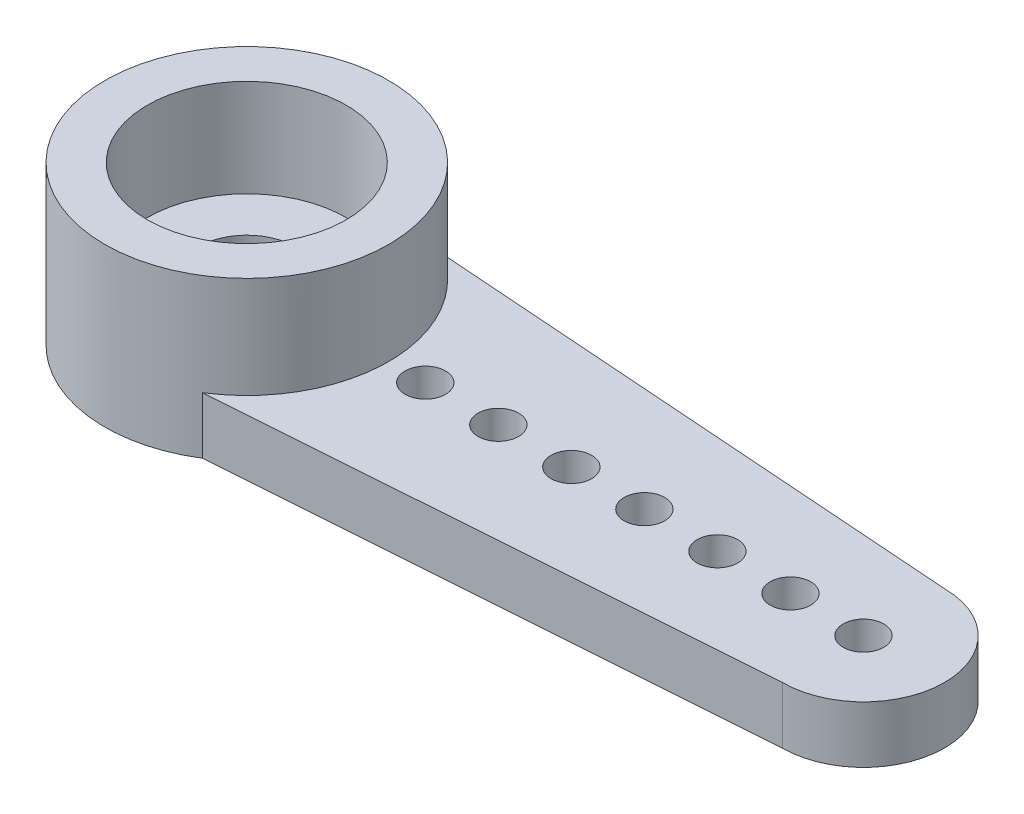
SolidWorks part; units mm, degrees
other "Camera1"
material "ABS"
ref_plane "Front Plane" through (0, 0, 0) normal (0, 0, 1) x (1, 0, 0)
ref_plane "Top Plane" through (0, 0, 0) normal (0, 1, 0) x (1, 0, 0)
ref_plane "Right Plane" through (0, 0, 0) normal (1, 0, 0) x (0, 0, -1)
sketch "Sketch1" plane through (0, 0, 0) normal (0, 1, 0) x (1, 0, 0)
  line L0 (-17.2, 0) -> (17.2, 0) construction
  line L1 (0, -8.35) -> (0, 8.35) construction
  line L2 (-15.2, 2) -> (-2, 2.95)
  line L3 (-15.2, -2) -> (-2, -2.95)
  line L4 (2, 6.35) -> (2, 3.5)
  line L5 (-2, 6.35) -> (-2, 2.95)
  line L6 (2, -6.35) -> (2, -3.5)
  line L7 (-2, -6.35) -> (-2, -2.95)
  line L8 (15.2, 2) -> (2, 3.5)
  line L9 (15.2, -2) -> (2, -3.5)
  circle A0 centre (0, 0) radius 3.5 construction
  arc A1 (-15.2, 2) -> (-15.2, -2) centre (-15.2, 0) ccw
  arc A2 (15.2, 2) -> (15.2, -2) centre (15.2, 0) cw
  arc A3 (2, 6.35) -> (-2, 6.35) centre (0, 6.35) ccw
  circle A4 centre (0, 6.35) radius 0.5
  circle A5 centre (0, 4.55) radius 0.5
  circle A6 centre (0, -4.55) radius 0.5
  circle A7 centre (0, -6.35) radius 0.5
  arc A8 (2, -6.35) -> (-2, -6.35) centre (0, -6.35) cw
  circle A10 centre (-15.2, 0) radius 0.5
  circle A11 centre (15.2, 0) radius 0.5
  circle A12 centre (-13.4, 0) radius 0.5
  circle A13 centre (-11.6, 0) radius 0.5
  circle A14 centre (-9.8, 0) radius 0.5
  circle A15 centre (-8, 0) radius 0.5
  circle A16 centre (-6.2, 0) radius 0.5
  circle A17 centre (-4.4, 0) radius 0.5
  circle A18 centre (13.4, 0) radius 0.5
  circle A19 centre (11.6, 0) radius 0.5
  circle A20 centre (9.8, 0) radius 0.5
  circle A21 centre (8, 0) radius 0.5
  circle A22 centre (6.2, 0) radius 0.5
  circle A23 centre (4.4, 0) radius 0.5
  point P5 (0, 0)
  point P8 (0, 0)
  point P25 (0, 6.85)
  point P26 (0, 4.05)
  dimension "D1" = 7
  dimension "D4" = 4
  dimension "D6" = 1
  dimension "D2" = 34.4
  dimension "D3" = 16.7
  dimension "D5" = 2
  dimension "D7" = 2.8
  dimension "D8" = 7
  dimension "D10" = 5.9
  dimension "D11" = 7
  dimension "D12" = 7
extrude "Boss-Extrude1" add sketch "Sketch1" along normal blind 1.4
sketch "Sketch2" plane through (0, 0, 0) normal (0, -1, 0) x (1, 0, 0)
  circle A0 centre (0, 0) radius 2.35
  dimension "D1" = 4.7
extrude "Cut-Extrude1" cut sketch "Sketch2" against normal blind 1
sketch "Sketch3" plane through (0, 1.4, 0) normal (0, 1, 0) x (1, 0, 0)
  circle A0 centre (0, 0) radius 2.45
  circle A1 centre (0, 0) radius 3.5
  dimension "D1" = 4.9
  dimension "D2" = 7
extrude "Boss-Extrude2" add sketch "Sketch3" along normal blind 2.5
sketch "Sketch4" plane through (0, 1.4, 0) normal (0, 1, 0) x (1, 0, 0)
  circle A0 centre (0, 0) radius 1.2
  dimension "D1" = 2.4
extrude "Cut-Extrude2" cut sketch "Sketch4" against normal through all
sketch "Sketch5" plane through (0, 1.4, 0) normal (0, 1, 0) x (1, 0, 0)
  circle A0 centre (0, 0) radius 1.2 construction
  circle A1 centre (0, 0) radius 2.45
  circle A2 centre (0, 0) radius 2.45
  circle A3 centre (0, 0) radius 1.2
  dimension "D1" = 0
extrude "Boss-Extrude3" add sketch "Sketch5" along normal blind 0.1
sketch "Sketch6" plane through (0, 0, 0) normal (0, -1, 0) x (1, 0, 0)
  line L0 (-2, -2.95) -> (-15.2, -2) construction
  line L1 (-1.8686, -2.9595) -> (-15.2, -2)
  line L2 (-15.2, 2) -> (-2, 2.95) construction
  line L3 (-15.2, 2) -> (-1.8686, 2.9595)
  line L4 (0, -9.3016) -> (0, 8.6978) construction
  line L5 (1.8686, -2.9595) -> (15.2, -2)
  line L6 (15.2, 2) -> (1.8686, 2.9595)
  line L8 (-17.8676, -8.836) -> (17.8676, -8.836)
  line L9 (-17.8676, -8.836) -> (-17.8676, 8.836)
  line L10 (-17.8676, 8.836) -> (17.8676, 8.836)
  line L11 (17.8676, -8.836) -> (17.8676, 8.836)
  line L12 (-17.8676, -8.836) -> (17.8676, 8.836) construction
  line L13 (-17.8676, 8.836) -> (17.8676, -8.836) construction
  arc A0 (-15.2, 2) -> (-15.2, -2) centre (-15.2, 0) ccw construction
  arc A1 (-15.2, 2) -> (-15.2, -2) centre (-15.2, 0) ccw
  circle A2 centre (0, 0) radius 3.5 construction
  arc A3 (1.8686, 2.9595) -> (-1.8686, 2.9595) centre (0, 0) ccw
  arc A4 (15.2, 2) -> (15.2, -2) centre (15.2, 0) cw
  arc A5 (-1.8686, -2.9595) -> (1.8686, -2.9595) centre (0, 0) ccw
extrude "Cut-Extrude4" cut sketch "Sketch6" against normal through all
sketch "Sketch7" [suppressed] plane through (0, 0, 0) normal (0, -1, 0) x (1, 0, 0)
  line L0 (0, 3.5) -> (-17.7318, 3.5)
  line L1 (-17.7318, 3.5) -> (-17.7318, -3.5)
  line L2 (-17.7318, -3.5) -> (0, -3.5)
  circle A0 centre (0, 0) radius 3.5 construction
  arc A1 (0, 3.5) -> (0, -3.5) centre (0, 0) ccw
extrude "Cut-Extrude5" [suppressed] cut sketch "Sketch7" against normal through all
sketch "Sketch8" plane through (0, 1.4, 0) normal (0, 1, 0) x (1, 0, 0)
  line L4 (-15.2, -2) -> (-1.8686, -2.9595)
  line L5 (-1.8686, 2.9595) -> (-15.2, 2)
  line L6 (-15.2, -2) -> (-1.8686, -2.9595)
  line L7 (-1.8686, 2.9595) -> (-15.2, 2)
  arc A4 (-1.8686, 2.9595) -> (-1.8686, -2.9595) centre (0, 0) ccw
  arc A5 (-15.2, 2) -> (-15.2, -2) centre (-15.2, 0) ccw
  arc A6 (-1.8686, 2.9595) -> (-1.8686, -2.9595) centre (0, 0) ccw
  arc A7 (-15.2, 2) -> (-15.2, -2) centre (-15.2, 0) ccw
  dimension "D1" = 0
extrude "Cut-Extrude6" cut sketch "Sketch8" against normal through all
